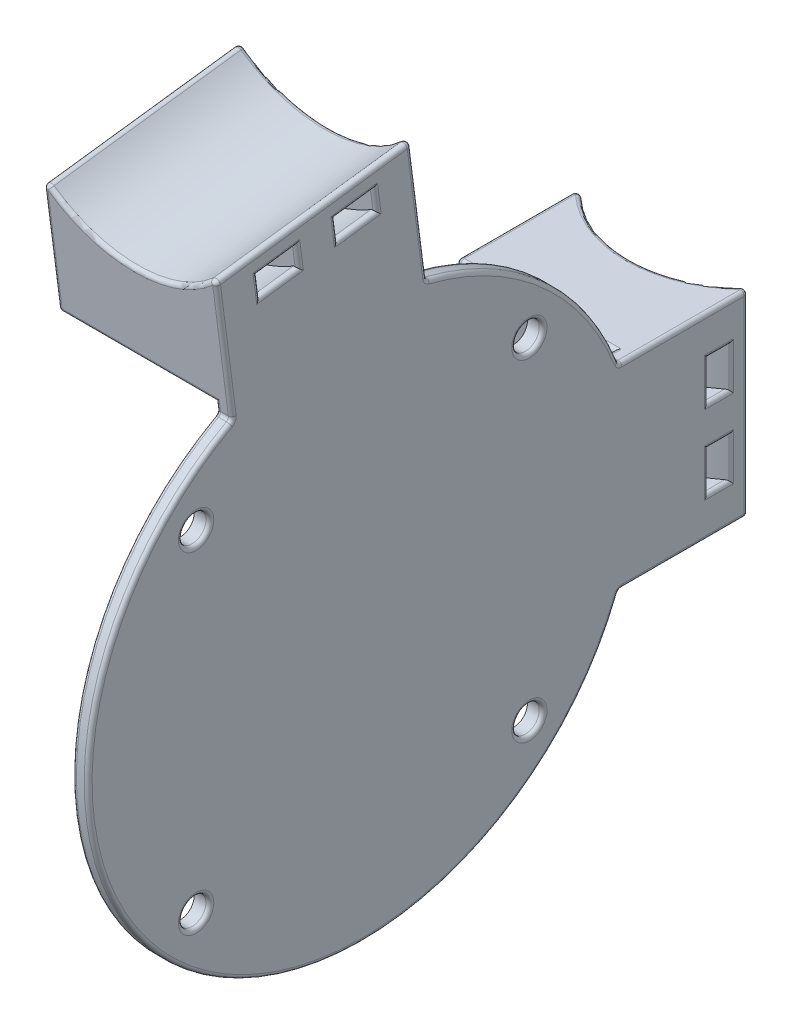
SolidWorks part; units mm, degrees
ref_plane "Front Plane" through (0, 0, 0) normal (0, 0, 1) x (1, 0, 0)
ref_plane "Top Plane" through (0, 0, 0) normal (0, 1, 0) x (1, 0, 0)
ref_plane "Right Plane" through (0, 0, 0) normal (1, 0, 0) x (0, 0, -1)
sketch "Sketch1" plane through (0, 0, 0) normal (1, 0, 0) x (0, 0, -1)
  circle A0 centre (0, 0) radius 35
  circle A1 centre (0, 35) radius 5
  circle A2 centre (35, 0) radius 5
  dimension "D1" = 70
  dimension "D2" = 10
extrude "Boss-Extrude1" add sketch "Sketch1" along normal blind 2 contours A2 A0 A1 | A0 A2 | A0 A2 | A0 A1 | A0 A1
sketch "Sketch2" plane through (2, 0, 0) normal (1, 0, 0) x (0, 0, -1)
  line L0 (-21.2369, 21.125) -> (21.2369, 21.125) construction
  line L1 (21.2369, 21.125) -> (21.2369, -21.125) construction
  line L2 (21.2369, -21.125) -> (-21.2369, -21.125) construction
  line L3 (-21.2369, -21.125) -> (-21.2369, 21.125) construction
  circle A0 centre (-21.2369, 21.125) radius 1.75
  circle A1 centre (21.2369, -21.125) radius 1.75
  circle A2 centre (21.2369, 21.125) radius 1.75
  circle A3 centre (-21.2369, -21.125) radius 1.75
  dimension "D1" = 3.5
  dimension "D2" = 42.4739
  dimension "D3" = 42.25
  dimension "D4" = 21.2369
  dimension "D5" = 21.125
extrude "Cut-Extrude1" cut sketch "Sketch2" against normal through all
sketch "Sketch3" plane through (0, 0, 0) normal (1, 0, 0) x (0, 0, -1)
  line L0 (-80.8104, 34.9318) -> (57.0977, 52.7524) construction
  line L1 (45, 58.983) -> (45, -30.9823) construction
  line L2 (-72.2874, 51.1578) -> (49515.419, 6458.917) construction
  line L3 (60, 43.1762) -> (60, -49956.8238) construction
  circle A0 centre (0, 0) radius 35 construction
  arc A1 (-4.9872, 34.6429) -> (34.6429, -4.9872) centre (0, 0) ccw construction
  circle A2 centre (0, 0) radius 45 construction
  dimension "D2" = 10
  dimension "D1" = 82.637
  dimension "D3" = 15
  dimension "D4" = 15
sketch "Sketch4" plane through (0, 0, 0) normal (1, 0, 0) x (0, 0, -1)
  line L0 (0, 12.5) -> (60, 12.5)
  line L1 (60, 12.5) -> (60, -12.5)
  line L2 (60, -12.5) -> (0, -12.5)
  line L3 (0, -12.5) -> (0, 12.5)
  line L4 (60, 200043.1762) -> (60, -249956.8238) construction
  line L5 (-12.3969, -1.6019) -> (-20.0862, 57.9033)
  line L6 (-20.0862, 57.9033) -> (4.7076, 61.1072)
  line L7 (4.7076, 61.1072) -> (12.3969, 1.6019)
  line L8 (12.3969, 1.6019) -> (-12.3969, -1.6019)
  line L10 (-198423.1129, -25579.8786) -> (247866.2445, 32089.9534) construction
  point P9 (1.4971, 60.6923)
  point P14 (-20.3867, 57.8645)
  dimension "D1" = 25
extrude "Boss-Extrude2" add sketch "Sketch4" along normal blind 2 contours L8 L3 L0 L7 L6 L5 | L7 L8 L3 L2 L1 L0
sketch "Sketch5" plane through (0, 0, 0) normal (-1, 0, 0) x (0, 0, 1)
  line L0 (-60, 12.5) -> (-60, -12.5)
  line L1 (-60, -12.5) -> (-30, -12.5)
  line L2 (-60, -12.5) -> (-32.6917, -12.5) construction
  line L3 (-30, -12.5) -> (-30, 12.5)
  line L4 (-32.6917, 12.5) -> (-60, 12.5) construction
  line L5 (-30, 12.5) -> (-60, 12.5)
  line L6 (-4.7076, 61.1072) -> (-8.5523, 31.3546)
  line L7 (-4.7076, 61.1072) -> (-8.2073, 34.0241) construction
  line L8 (-8.5523, 31.3546) -> (16.2416, 28.1507)
  line L9 (16.5865, 30.8202) -> (20.0862, 57.9033) construction
  line L10 (16.2416, 28.1507) -> (20.0862, 57.9033)
  line L11 (20.0862, 57.9033) -> (-4.7076, 61.1072)
  circle A0 centre (0, 0) radius 30 construction
  circle A2 centre (0, 0) radius 35 construction
  dimension "D1" = 5
extrude "Boss-Extrude3" add sketch "Sketch5" along normal blind 20
sketch "Sketch7" plane through (0, 12.5, 0) normal (0, 1, 0) x (1, 0, 0)
  line L0 (2, 60) -> (-20, 60) construction
  circle A0 centre (-9, 60) radius 15
  point P2 (0, 0)
  point P3 (-9, 60)
  dimension "D1" = 30
extrude "Cut-Extrude2" cut sketch "Sketch7" against normal through all both and the other way through all
sketch "Sketch8" plane through (0, 1.6019, -12.3969) normal (0, 0.1282, -0.9918) x (-1, 0, 0)
  line L0 (-2, 60) -> (20, 60) construction
  circle A0 centre (9, 60) radius 15
  point P2 (9, 60)
  dimension "D1" = 30
extrude "Cut-Extrude3" cut sketch "Sketch8" against normal through all both and the other way through all
sketch "Sketch9" plane through (0, 0, 0) normal (0, 1, 0) x (1, 0, 0)
  line L0 (-34.9153, 0) -> (20.9649, 0) construction
  line L1 (-20, 42.5595) -> (0, 36)
  line L2 (-20, 49.802) -> (-20, 30) construction
  line L3 (0, -198423.1129) -> (0, 247866.2445) construction
  line L5 (-20, 0) -> (-20, 42.5595)
  line L6 (0, 36) -> (0, 0)
  line L7 (0, 0) -> (-20, 0)
  line L8 (0, 36) -> (-20, 36)
  circle A0 centre (-9, 60) radius 15 construction
  arc A1 (-20, 49.802) -> (2, 49.802) centre (-9, 60) ccw construction
  circle A2 centre (-9, 60) radius 20 construction
  dimension "D2" = 5
  dimension "D1" = 36
revolve "Cut-Revolve1" cut sketch "Sketch9" angle 360 about L0
ref_plane "Plane1" through (-9, 0, 0) normal (1, 0, 0) x (0, 0, -1)
sketch "Sketch11" plane through (-9, 0, 0) normal (1, 0, 0) x (0, 0, -1)
  line L0 (60, 45.9472) -> (60, -50.0875) construction
  line L1 (60, 200043.1762) -> (60, -249956.8238) construction
  line L2 (42, 12.5) -> (42, 7.5) construction
  line L3 (43, 7.5) -> (41, 7.5)
  line L4 (43, 7.5) -> (43, 2.5)
  line L5 (43, 2.5) -> (41, 2.5)
  line L6 (41, 7.5) -> (41, 2.5)
  line L7 (43, -2.5) -> (41, -2.5)
  line L8 (43, -2.5) -> (43, -7.5)
  line L9 (43, -7.5) -> (41, -7.5)
  line L10 (41, -2.5) -> (41, -7.5)
  line L11 (33.7602, 12.5) -> (49.802, 12.5) construction
  line L12 (42, 2.5) -> (42, -2.5) construction
  line L13 (42, -7.5) -> (42, -12.5) construction
  line L14 (49.802, -12.5) -> (33.7602, -12.5) construction
  line L15 (45, 200058.983) -> (45, -200030.9823) construction
  point P22 (43.6123, 2.1684)
  point P23 (43.6123, -4.369)
  dimension "D1" = 2
  dimension "D2" = 2
  dimension "D3" = 5
revolve "Cut-Revolve2" cut sketch "Sketch11" angle 360 about L0
sketch "Sketch12" plane through (-9, 0, 0) normal (1, 0, 0) x (0, 0, -1)
  line L0 (-55.9471, 53.2693) -> (39.2957, 65.5767) construction
  line L1 (-16.7235, 31.8799) -> (-18.7793, 47.7894) construction
  line L2 (-17.7794, 40.0517) -> (-12.8207, 40.6925) construction
  line L3 (-12.9488, 41.6843) -> (-12.6925, 39.7008)
  line L4 (-12.9488, 41.6843) -> (-7.9901, 42.325)
  line L5 (-7.9901, 42.325) -> (-7.7337, 40.3415)
  line L6 (-12.6925, 39.7008) -> (-7.7337, 40.3415)
  line L7 (-3.0313, 42.9658) -> (-2.775, 40.9823)
  line L8 (-3.0313, 42.9658) -> (1.9275, 43.6066)
  line L9 (1.9275, 43.6066) -> (2.1838, 41.6231)
  line L10 (-2.775, 40.9823) -> (2.1838, 41.6231)
  line L11 (-198431.6359, -25596.1047) -> (198407.9232, 25683.7888) construction
  line L12 (-7.8619, 41.3333) -> (-2.9031, 41.9741) construction
  line L13 (2.0556, 42.6148) -> (7.0144, 43.2556) construction
  line L16 (-198423.1129, -25579.8786) -> (247866.2445, 32089.9534) construction
  line L17 (6.0145, 50.9932) -> (8.0704, 35.0837) construction
  point P18 (6.9423, 43.8135)
  point P21 (0, 0)
  point P22 (7.0144, 43.2553)
  point P23 (-17.7605, 39.9049)
  dimension "D1" = 2
  dimension "D2" = 2
  dimension "D3" = 5
revolve "Cut-Revolve3" cut sketch "Sketch12" angle 360 about L0
fillet "Fillet1" radius 0.5 70 edges at (2, -21.125, 19.4869) (2, 21.125, 19.4869) (2, -21.125, -22.9869) (2, 21.125, -22.9869) (2, 45.7162, 3.3867) (2, 46.357, -1.5721) (2, 47.2914, 1.0695) (2, 44.4347, 13.3042) (2, 43.5003, 10.6627) (2, 45.0755, 8.3455) (2, 46.0099, 10.987) (2, 44.7818, 0.7452) (2, 7.5, -45.7733) (2, -5, -44.5081) (2, -7.5, -45.7733) (2, -2.5, -45.7733) (2, 5, -47.0385) (2, 2.5, -45.7733) (2, 5, -44.5081) (2, -5, -47.0385) (-20, -2.5, -45.7733) (-20, -5, -44.5081) (-20, -7.5, -45.7733) (-20, 7.5, -45.7733) (-20, 5, -44.5081) (-20, 2.5, -45.7733) (-20, 5, -47.0385) (-20, 45.7162, 3.3867) (-20, 44.7818, 0.7452) (-20, 46.357, -1.5721) (-20, 47.2914, 1.0695) (-20, 44.4347, 13.3042) (-20, 43.5003, 10.6627) (-20, 45.0755, 8.3455) (-20, 46.0099, 10.987) (-20, -5, -47.0385) (-9, 12.5, -45) (-20, 12.5, -41.7811) (-9, -12.5, -45) (-20, -12.5, -41.7811) (-20, 39.8346, 17.7514) (-20, 43.0385, -7.0425) (0, 31.35, 16.655) (2, 39.3048, 17.6829) (0, 12.5, -33.226) (2, 12.5, -41.2469) (0, -12.5, -33.226) (2, -12.5, -41.2469) (0, 34.5539, -8.1388) (2, 42.5087, -7.1109) (-9, 43.027, 18.1639) (-9, 46.2309, -6.6299) (-20, 49.3913, 6.3824) (2, 49.3913, 6.3824) (2, 26.2868, -23.1085) (2, -26.2868, 23.1085) (2, 0, -49.802) (-20, 0, -49.802) (0, 26.2868, -23.1085) (0, -26.2868, 23.1085) (1, 34.0241, -8.2073) (1, 12.5, -32.6917) (1, 30.8202, 16.5865) (1, -12.5, -32.6917) (-10, 31.8799, 16.7235) (-20, 35.7031, 4.6136) (-10, 35.0837, -8.0704) (-10, 12.5, -33.7602) (-10, -12.5, -33.7602) (-20, 0, -36)
